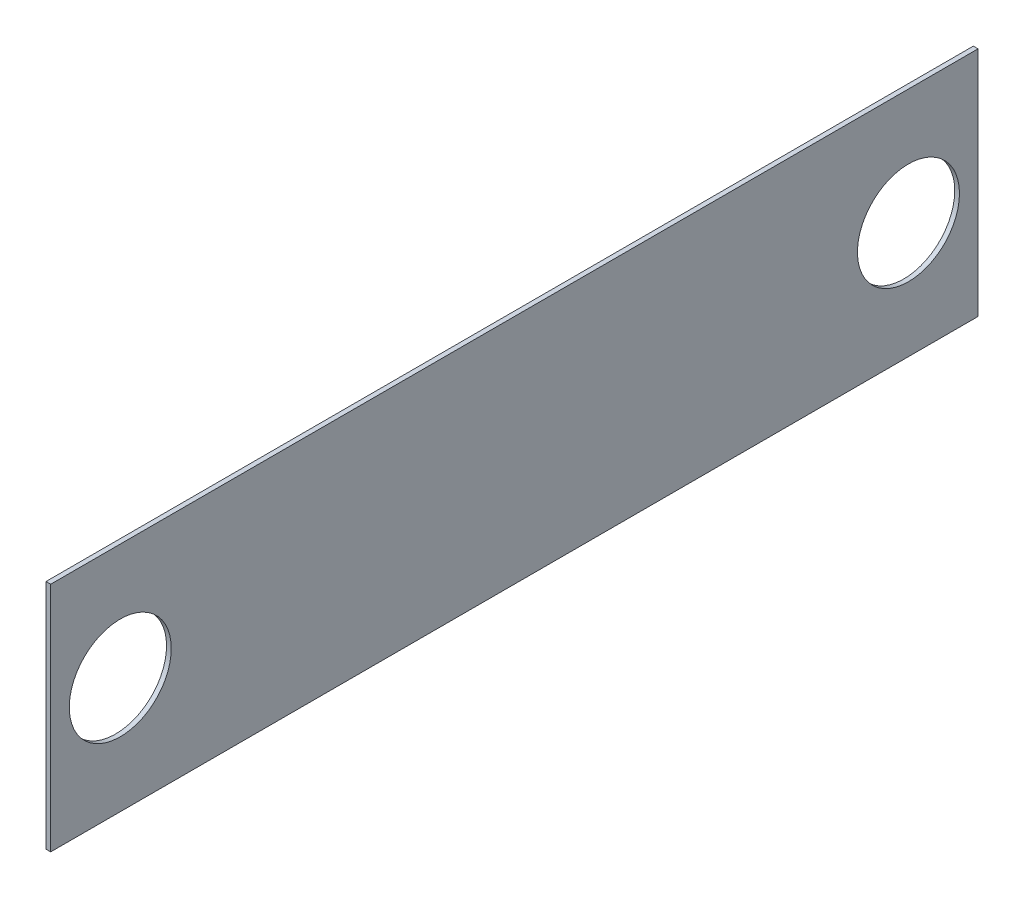
SolidWorks part; units mm, degrees
material "Low Carbon Steel"
ref_plane "Front Plane" through (0, 0, 0) normal (0, 0, 1) x (1, 0, 0)
ref_plane "Top Plane" through (0, 0, 0) normal (0, 1, 0) x (1, 0, 0)
ref_plane "Right Plane" through (0, 0, 0) normal (1, 0, 0) x (0, 0, -1)
sketch "Sketch1" plane through (0, 0, 0) normal (1, 0, 0) x (0, 0, -1)
  line L0 (-50, -12.5) -> (50, 12.5) construction
  line L1 (-50, 12.5) -> (50, 12.5)
  line L2 (-50, 12.5) -> (-50, -12.5)
  line L3 (-50, -12.5) -> (50, -12.5)
  line L4 (50, 12.5) -> (50, -12.5)
  dimension "D1" = 100
  dimension "D2" = 25
extrude "Boss-Extrude1" add sketch "Sketch1" along normal blind 0.508
hole_wizard "M10 Clearance Hole1" positions "Sketch2" profile "Sketch3" hole size "M10" standard "Peddi DIN" end condition through all
sketch "Sketch2" plane through (0.508, 0, 0) normal (1, 0, 0) x (0, 0, -1)
  line L0 (42.5, 0) -> (-42.5, 0) construction
  point P0 (-42.5, 0)
  point P2 (42.5, 0)
  dimension "D1" = 85
sketch "Sketch3" plane through (0.508, 0, 42.5) normal (0, 1, 0) x (0, 0, -1)
  line L0 (0, 0) -> (0, 0.508)
  line L1 (0, 0.508) -> (5.5, 0.508)
  line L2 (5.5, 0.508) -> (5.5, 0)
  line L5 (5.5, 0) -> (0, 0)
  line L11 (0, -6.35) -> (0, 107.95) construction
  dimension "Thru Hole Dia." = 11
  dimension "Thru Hole Depth" = 0.508
other "Freeze***"
